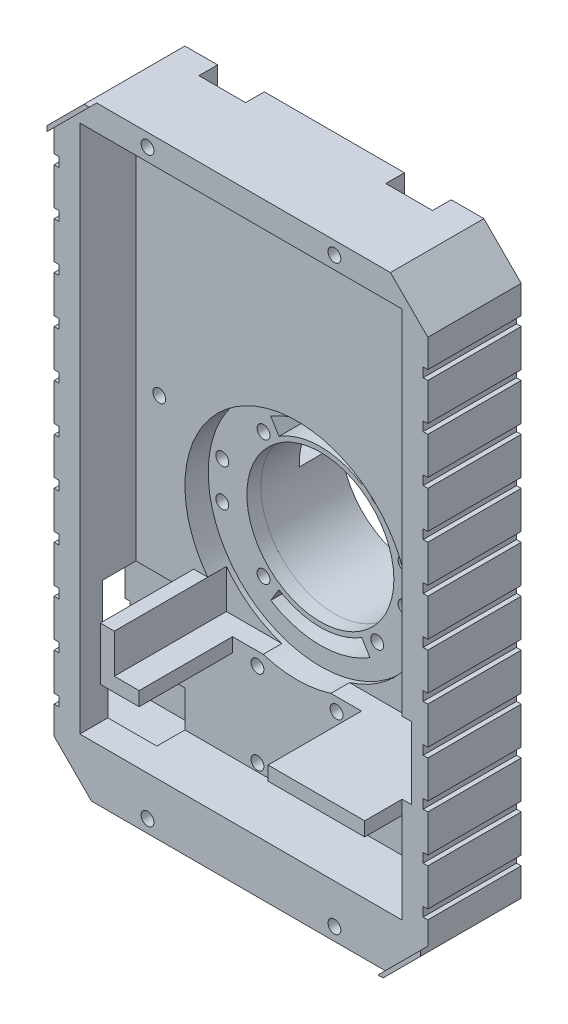
SolidWorks part; units mm, degrees
ref_plane "Front Plane" through (0, 0, 0) normal (0, 0, 1) x (1, 0, 0)
ref_plane "Top Plane" through (0, 0, 0) normal (0, 1, 0) x (1, 0, 0)
ref_plane "Right Plane" through (0, 0, 0) normal (1, 0, 0) x (0, 0, -1)
sketch "Sketch1" plane through (0, 0, 0) normal (0, 0, 1) x (1, 0, 0)
  line L1 (-50.8, -82.55) -> (50.8, -82.55)
  line L2 (-50.8, -82.55) -> (-50.8, 82.55)
  line L3 (-50.8, 82.55) -> (50.8, 82.55)
  line L4 (50.8, -82.55) -> (50.8, 82.55)
  line L5 (-50.8, -82.55) -> (50.8, 82.55) construction
  line L6 (-50.8, 82.55) -> (50.8, -82.55) construction
  point P0 (0, 0)
  dimension "D1" = 101.6
  dimension "D2" = 165.1
extrude "Boss-Extrude1" add sketch "Sketch1" along normal blind 25.4
sketch "Sketch2" plane through (0, 0, 25.4) normal (0, 0, 1) x (1, 0, 0)
  line L0 (50.8, 82.55) -> (-50.8, 82.55) construction
  line L1 (-43.8, -68.326) -> (43.8, -68.326)
  line L2 (-43.8, -68.326) -> (-43.8, 75.55)
  line L3 (-43.8, 75.55) -> (43.8, 75.55)
  line L4 (43.8, -68.326) -> (43.8, 75.55)
  line L5 (-43.8, -68.326) -> (43.8, 75.55) construction
  line L6 (-43.8, 75.55) -> (43.8, -68.326) construction
  line L7 (50.8, -82.55) -> (50.8, 82.55) construction
  line L8 (-50.8, -82.55) -> (50.8, -82.55) construction
  point P0 (0, 0)
  dimension "D1" = 7
  dimension "D2" = 7
  dimension "D3" = 143.876
  dimension "D4" = 87.6
  dimension "D5" = 14.224
extrude "Cut-Extrude1" cut sketch "Sketch2" against normal blind 15.24
sketch "Sketch3" plane through (0, 0, 10.16) normal (0, 0, 1) x (1, 0, 0)
  circle A0 centre (0, -10.8184) radius 19.9875
  dimension "D1" = 39.975
extrude "Cut-Extrude2" cut sketch "Sketch3" against normal through all
sketch "Sketch4" plane through (0, 0, 0) normal (0, 0, -1) x (-1, 0, 0)
  circle A0 centre (0, -10.8184) radius 19.9875
  circle A1 centre (0, -10.8184) radius 26.9875
  dimension "D1" = 53.975
  dimension "D2" = 7
  dimension "D3" = 39.975
extrude "Boss-Extrude2" add sketch "Sketch4" along normal blind 21.844
sketch "Sketch6" plane through (0, 0, -20.955) normal (0, 0, -1) x (-1, 0, 0)
  circle A0 centre (15.4528, 6.1996) radius 1.75
  circle A1 centre (15.4528, -27.8364) radius 1.75
  circle A2 centre (-15.4528, 6.1996) radius 1.75
  circle A3 centre (-15.4528, -27.8364) radius 1.75
  circle A4 centre (0, -10.8184) radius 26.9875 construction
  circle A5 centre (0, -10.8184) radius 26.7375 construction
  dimension "D1" = 3.5
  dimension "D2" = 3.5
  dimension "D3" = 22.987
  dimension "D4" = 22.987
  dimension "D7" = 3.5
  dimension "D8" = 3.5
  dimension "D9" = 22.987
  dimension "D10" = 22.987
extrude "Cut-Extrude3" cut sketch "Sketch6" against normal through all both and the other way through all
sketch "Sketch7" plane through (0, 0, 25.4) normal (0, 0, 1) x (1, 0, 0)
  line L0 (50.8, 82.55) -> (-50.8, 82.55) construction
  line L1 (-50.8, 82.55) -> (-50.8, -82.55) construction
  line L2 (50.8, -82.55) -> (50.8, 82.55) construction
  line L3 (-50.8, -82.55) -> (50.8, -82.55) construction
  circle A0 centre (-25.4, 79.05) radius 1.75
  circle A1 centre (25.4, -79.05) radius 1.75
  circle A2 centre (-25.4, -79.05) radius 1.75
  circle A3 centre (25.4, 79.05) radius 1.75
  dimension "D1" = 3.5
  dimension "D2" = 3.5
  dimension "D3" = 3.5
  dimension "D4" = 3.5
  dimension "D5" = 25.4
  dimension "D6" = 25.4
  dimension "D7" = 25.4
  dimension "D8" = 3.5
  dimension "D9" = 3.5
  dimension "D10" = 3.5
  dimension "D11" = 3.5
  dimension "D12" = 25.4
extrude "Cut-Extrude4" cut sketch "Sketch7" against normal through all
sketch "Sketch8" plane through (0, 0, 0) normal (0, 0, -1) x (-1, 0, 0)
  line L1 (-50.8, 82.55) -> (50.8, 82.55) construction
  line L7 (19.05, 75.55) -> (31.75, 75.55)
  line L8 (50.8, -82.55) -> (-50.8, -82.55) construction
  line L14 (-31.75, 75.55) -> (-19.05, 75.55)
  line L15 (-31.75, 75.55) -> (-31.75, 82.55)
  line L16 (-31.75, 82.55) -> (-19.05, 82.55)
  line L17 (-19.05, 75.55) -> (-19.05, 82.55)
  line L18 (-31.75, 75.55) -> (-19.05, 82.55) construction
  line L19 (-31.75, 82.55) -> (-19.05, 75.55) construction
  line L20 (19.05, -75.55) -> (31.75, -75.55)
  line L21 (19.05, -75.55) -> (19.05, -82.55)
  line L22 (19.05, -82.55) -> (31.75, -82.55)
  line L23 (31.75, -75.55) -> (31.75, -82.55)
  line L24 (19.05, -75.55) -> (31.75, -82.55) construction
  line L25 (19.05, -82.55) -> (31.75, -75.55) construction
  line L26 (19.05, 75.55) -> (19.05, 82.55)
  line L27 (19.05, 82.55) -> (31.75, 82.55)
  line L28 (31.75, 75.55) -> (31.75, 82.55)
  line L29 (19.05, 75.55) -> (31.75, 82.55) construction
  line L30 (19.05, 82.55) -> (31.75, 75.55) construction
  line L31 (-31.75, -75.55) -> (-19.05, -75.55)
  line L32 (-31.75, -75.55) -> (-31.75, -82.55)
  line L33 (-31.75, -82.55) -> (-19.05, -82.55)
  line L34 (-19.05, -75.55) -> (-19.05, -82.55)
  line L35 (-31.75, -75.55) -> (-19.05, -82.55) construction
  line L36 (-31.75, -82.55) -> (-19.05, -75.55) construction
  circle A0 centre (-25.4, 79.05) radius 1.75 construction
  circle A4 centre (25.4, -79.05) radius 1.75 construction
  point P2 (25.4, 79.05)
  point P4 (-25.4, 79.05)
  point P13 (-25.4, -79.05)
  point P14 (25.4, -79.05)
  dimension "D7" = 12.7
  dimension "D1" = 12.7
  dimension "D2" = 12.7
  dimension "D3" = 7
  dimension "D4" = 7
  dimension "D5" = 0
  dimension "D6" = 0
  dimension "D8" = 12.7
extrude "Cut-Extrude5" cut sketch "Sketch8" against normal blind 5.08
sketch "Sketch9" plane through (0, 0, 0) normal (1, 0, 0) x (0, 0, -1)
  line L2 (21.844, -37.8059) -> (21.844, 16.1691) construction
  line L8 (8.1915, 1.8816) -> (21.844, 1.8816)
  line L9 (8.1915, 1.8816) -> (8.1915, -23.5184)
  line L10 (8.1915, -23.5184) -> (21.844, -23.5184)
  line L11 (21.844, 1.8816) -> (21.844, -23.5184)
extrude "Cut-Extrude6" cut sketch "Sketch9" along normal through all
sketch "Sketch10" plane through (0, 0, 0) normal (1, 0, 0) x (0, 0, -1)
  line L0 (21.844, -30.8059) -> (21.844, 9.1691) construction
  line L8 (8.1915, -23.5184) -> (21.844, -23.5184) construction
  line L10 (10.414, -0.0234) -> (10.414, -11.4534)
  line L13 (21.844, -0.0234) -> (21.844, -11.4534)
  line L14 (10.414, -0.0234) -> (21.844, -0.0234)
  line L15 (21.844, -11.4534) -> (10.414, -11.4534)
  dimension "D1" = 11.43
  dimension "D2" = 11.43
  dimension "D3" = 12.065
extrude "Cut-Extrude7" cut sketch "Sketch10" against normal through all
sketch "Sketch11" plane through (0, 0, 10.16) normal (0, 0, 1) x (1, 0, 0)
  circle A1 centre (0, -10.8184) radius 30.48
  dimension "D1" = 60.96
extrude "Cut-Extrude8" cut sketch "Sketch11" against normal blind 6.35
sketch "Sketch12" plane through (0, 0, -21.844) normal (0, 0, -1) x (-1, 0, 0)
  line L0 (-13.4968, 10.8532) -> (-11.2502, 7.2458)
  line L1 (11.2502, 7.2458) -> (13.4968, 10.8532)
  line L2 (-13.4968, -32.49) -> (-11.2502, -28.8826)
  line L4 (11.2502, -28.8826) -> (13.4968, -32.49)
  circle A8 centre (-15.4528, 6.1996) radius 1.75 construction
  circle A9 centre (15.4528, 6.1996) radius 1.75 construction
  arc A10 (-11.2502, -28.8826) -> (11.2502, -28.8826) centre (0, -10.8184) ccw
  arc A11 (-13.4968, -32.49) -> (13.4968, -32.49) centre (0, -10.8184) ccw
  circle A12 centre (-15.4528, -27.8364) radius 1.75 construction
  circle A13 centre (15.4528, -27.8364) radius 1.75 construction
  arc A14 (11.2502, 7.2458) -> (-11.2502, 7.2458) centre (0, -10.8184) ccw
  arc A15 (13.4968, 10.8532) -> (-13.4968, 10.8532) centre (0, -10.8184) ccw
  dimension "D2" = 4.1205
  dimension "D3" = 4.1205
  dimension "D4" = 4.1205
  dimension "D6" = 4.1205
extrude "Cut-Extrude9" cut sketch "Sketch12" against normal up to next
sketch "Sketch13" plane through (0, 0, 0) normal (0, 0, -1) x (-1, 0, 0)
  line L0 (-50.8, -82.55) -> (-50.8, 82.55) construction
  line L1 (-52.07, -62.23) -> (-49.53, -62.23)
  line L2 (-52.07, -62.23) -> (-52.07, -64.77)
  line L3 (-52.07, -64.77) -> (-49.53, -64.77)
  line L4 (-49.53, -62.23) -> (-49.53, -64.77)
  line L5 (-52.07, -62.23) -> (-49.53, -64.77) construction
  line L6 (-52.07, -64.77) -> (-49.53, -62.23) construction
  line L7 (-49.53, -49.53) -> (-49.53, -52.07)
  line L8 (-52.07, -52.07) -> (-49.53, -52.07)
  line L9 (-52.07, -49.53) -> (-52.07, -52.07)
  line L10 (-52.07, -49.53) -> (-49.53, -49.53)
  line L11 (-49.53, -36.83) -> (-49.53, -39.37)
  line L12 (-52.07, -39.37) -> (-49.53, -39.37)
  line L13 (-52.07, -36.83) -> (-52.07, -39.37)
  line L14 (-52.07, -36.83) -> (-49.53, -36.83)
  line L15 (-49.53, -24.13) -> (-49.53, -26.67)
  line L16 (-52.07, -26.67) -> (-49.53, -26.67)
  line L17 (-52.07, -24.13) -> (-52.07, -26.67)
  line L18 (-52.07, -24.13) -> (-49.53, -24.13)
  line L19 (-49.53, -11.43) -> (-49.53, -13.97)
  line L20 (-52.07, -13.97) -> (-49.53, -13.97)
  line L21 (-52.07, -11.43) -> (-52.07, -13.97)
  line L22 (-52.07, -11.43) -> (-49.53, -11.43)
  line L23 (-49.53, 1.27) -> (-49.53, -1.27)
  line L24 (-52.07, -1.27) -> (-49.53, -1.27)
  line L25 (-52.07, 1.27) -> (-52.07, -1.27)
  line L26 (-52.07, 1.27) -> (-49.53, 1.27)
  line L27 (-49.53, 13.97) -> (-49.53, 11.43)
  line L28 (-52.07, 11.43) -> (-49.53, 11.43)
  line L29 (-52.07, 13.97) -> (-52.07, 11.43)
  line L30 (-52.07, 13.97) -> (-49.53, 13.97)
  line L31 (-49.53, 26.67) -> (-49.53, 24.13)
  line L32 (-52.07, 24.13) -> (-49.53, 24.13)
  line L33 (-52.07, 26.67) -> (-52.07, 24.13)
  line L34 (-52.07, 26.67) -> (-49.53, 26.67)
  line L35 (-49.53, 39.37) -> (-49.53, 36.83)
  line L36 (-52.07, 36.83) -> (-49.53, 36.83)
  line L37 (-52.07, 39.37) -> (-52.07, 36.83)
  line L38 (-52.07, 39.37) -> (-49.53, 39.37)
  line L39 (-49.53, 52.07) -> (-49.53, 49.53)
  line L40 (-52.07, 49.53) -> (-49.53, 49.53)
  line L41 (-52.07, 52.07) -> (-52.07, 49.53)
  line L42 (-52.07, 52.07) -> (-49.53, 52.07)
  line L43 (-49.53, 64.77) -> (-49.53, 62.23)
  line L44 (-52.07, 62.23) -> (-49.53, 62.23)
  line L45 (-52.07, 64.77) -> (-52.07, 62.23)
  line L46 (-52.07, 64.77) -> (-49.53, 64.77)
  line L55 (50.8, 82.55) -> (50.8, -82.55) construction
  line L56 (49.53, -64.77) -> (52.07, -64.77)
  line L57 (49.53, -64.77) -> (49.53, -62.23)
  line L58 (49.53, -62.23) -> (52.07, -62.23)
  line L59 (52.07, -64.77) -> (52.07, -62.23)
  line L60 (49.53, -64.77) -> (52.07, -62.23) construction
  line L61 (49.53, -62.23) -> (52.07, -64.77) construction
  line L62 (49.53, -52.07) -> (49.53, -49.53)
  line L63 (49.53, -49.53) -> (52.07, -49.53)
  line L64 (52.07, -52.07) -> (52.07, -49.53)
  line L65 (49.53, -52.07) -> (52.07, -52.07)
  line L66 (49.53, -39.37) -> (49.53, -36.83)
  line L67 (49.53, -36.83) -> (52.07, -36.83)
  line L68 (52.07, -39.37) -> (52.07, -36.83)
  line L69 (49.53, -39.37) -> (52.07, -39.37)
  line L70 (49.53, -26.67) -> (49.53, -24.13)
  line L71 (49.53, -24.13) -> (52.07, -24.13)
  line L72 (52.07, -26.67) -> (52.07, -24.13)
  line L73 (49.53, -26.67) -> (52.07, -26.67)
  line L74 (49.53, -13.97) -> (49.53, -11.43)
  line L75 (49.53, -11.43) -> (52.07, -11.43)
  line L76 (52.07, -13.97) -> (52.07, -11.43)
  line L77 (49.53, -13.97) -> (52.07, -13.97)
  line L78 (49.53, -1.27) -> (49.53, 1.27)
  line L79 (49.53, 1.27) -> (52.07, 1.27)
  line L80 (52.07, -1.27) -> (52.07, 1.27)
  line L81 (49.53, -1.27) -> (52.07, -1.27)
  line L82 (49.53, 11.43) -> (49.53, 13.97)
  line L83 (49.53, 13.97) -> (52.07, 13.97)
  line L84 (52.07, 11.43) -> (52.07, 13.97)
  line L85 (49.53, 11.43) -> (52.07, 11.43)
  line L86 (49.53, 24.13) -> (49.53, 26.67)
  line L87 (49.53, 26.67) -> (52.07, 26.67)
  line L88 (52.07, 24.13) -> (52.07, 26.67)
  line L89 (49.53, 24.13) -> (52.07, 24.13)
  line L90 (49.53, 36.83) -> (49.53, 39.37)
  line L91 (49.53, 39.37) -> (52.07, 39.37)
  line L92 (52.07, 36.83) -> (52.07, 39.37)
  line L93 (49.53, 36.83) -> (52.07, 36.83)
  line L94 (49.53, 49.53) -> (49.53, 52.07)
  line L95 (49.53, 52.07) -> (52.07, 52.07)
  line L96 (52.07, 49.53) -> (52.07, 52.07)
  line L97 (49.53, 49.53) -> (52.07, 49.53)
  line L98 (49.53, 62.23) -> (49.53, 64.77)
  line L99 (49.53, 64.77) -> (52.07, 64.77)
  line L100 (52.07, 62.23) -> (52.07, 64.77)
  line L101 (49.53, 62.23) -> (52.07, 62.23)
  line L110 (-49.53, 77.47) -> (-49.53, 74.93) [skipped]
  line L111 (-52.07, 74.93) -> (-49.53, 74.93) [skipped]
  line L112 (-52.07, 77.47) -> (-52.07, 74.93) [skipped]
  line L113 (-52.07, 77.47) -> (-49.53, 77.47) [skipped]
  line L114 (-49.53, 90.17) -> (-49.53, 87.63) [skipped]
  line L115 (-52.07, 87.63) -> (-49.53, 87.63) [skipped]
  line L116 (-52.07, 90.17) -> (-52.07, 87.63) [skipped]
  line L117 (-52.07, 90.17) -> (-49.53, 90.17) [skipped]
  line L118 (49.53, 74.93) -> (49.53, 77.47) [skipped]
  line L119 (49.53, 77.47) -> (52.07, 77.47) [skipped]
  line L120 (52.07, 74.93) -> (52.07, 77.47) [skipped]
  line L121 (49.53, 74.93) -> (52.07, 74.93) [skipped]
  line L122 (49.53, 87.63) -> (49.53, 90.17) [skipped]
  line L123 (49.53, 90.17) -> (52.07, 90.17) [skipped]
  line L124 (52.07, 87.63) -> (52.07, 90.17) [skipped]
  line L125 (49.53, 87.63) -> (52.07, 87.63) [skipped]
  point P0 (-50.8, -63.5)
  point P8 (50.8, -63.5)
  dimension "D1" = 2.54
  dimension "D2" = 2.54
  dimension "D3" = 17.78
  dimension "D5" = 2.54
  dimension "D6" = 2.54
  dimension "D7" = 17.78
  dimension "D9" = 10.16
  dimension "D4" = 13
  dimension "D8" = 13
extrude "Cut-Extrude10" cut sketch "Sketch13" against normal up to next
chamfer "Chamfer9" distance 10.16 angle 45 4 edges at (50.8, 82.55, 12.7) (50.8, -82.55, 12.7) (-50.8, -82.55, 12.7) (-50.8, 82.55, 12.7)
sketch "Sketch14" plane through (0, 0, 3.81) normal (0, 0, 1) x (1, 0, 0)
  circle A2 centre (-26.67, -5.7384) radius 1.75
  circle A3 centre (-26.67, -15.8984) radius 1.75
  circle A4 centre (0, -10.8184) radius 19.9875 construction
  circle A5 centre (22.86, -5.7384) radius 1.75
  circle A6 centre (22.86, -15.8984) radius 1.75
  dimension "D1" = 26.67
  dimension "D2" = 26.67
  dimension "D3" = 3.5
  dimension "D4" = 3.5
  dimension "D6" = 22.86
  dimension "D7" = 3.5
  dimension "D8" = 3.5
  dimension "D5" = 22.86
extrude "Cut-Extrude11" cut sketch "Sketch14" against normal blind 2.54
sketch "Sketch15" plane through (0, 0, 10.16) normal (0, 0, 1) x (1, 0, 0)
  line L0 (-43.8, 75.55) -> (-43.8, -68.326) construction
  line L1 (43.8, 75.55) -> (-43.8, 75.55) construction
  line L2 (43.8, -68.326) -> (43.8, 75.55) construction
  circle A0 centre (-37.45, 69.2) radius 1.75
  circle A1 centre (-37.45, 6.9216) radius 1.75
  circle A2 centre (38.085, 69.2) radius 1.75
  circle A3 centre (38.085, 6.9216) radius 1.75
  dimension "D1" = 3.5
  dimension "D2" = 3.5
  dimension "D3" = 3.5
  dimension "D4" = 3.5
  dimension "D5" = 6.35
  dimension "D6" = 6.35
  dimension "D7" = 6.35
  dimension "D8" = 5.715
  dimension "D9" = 6.35
  dimension "D10" = 5.715
extrude "Cut-Extrude12" cut sketch "Sketch15" against normal blind 5.08
sketch "Sketch16" plane through (0, 0, 25.4) normal (0, 0, 1) x (1, 0, 0)
  line L2 (-45.0129, 76.7629) -> (-50.8, 70.9758)
  line L3 (-50.8, 72.39) -> (-50.8, 64.77) construction
  line L4 (-50.8, 70.9758) -> (-50.8, 72.39)
  line L5 (-50.8, 72.39) -> (-40.64, 82.55)
  line L6 (-45.0129, 76.7629) -> (-39.2258, 82.55)
  line L7 (40.64, 82.55) -> (-40.64, 82.55) construction
  line L8 (-39.2258, 82.55) -> (-40.64, 82.55)
  line L10 (45.0129, -76.7629) -> (39.2258, -82.55)
  line L11 (-40.64, -82.55) -> (40.64, -82.55) construction
  line L12 (39.2258, -82.55) -> (40.64, -82.55)
  line L13 (40.64, -82.55) -> (50.8, -72.39)
  line L14 (45.0129, -76.7629) -> (50.8, -70.9758)
  line L15 (50.8, -72.39) -> (50.8, -64.77) construction
  line L16 (50.8, -70.9758) -> (50.8, -72.39)
extrude "Boss-Extrude3" add sketch "Sketch16" along normal blind 2
sketch "Sketch18" plane through (-50.8, 0, 0) normal (-1, 0, 0) x (0, 0, 1)
  line L0 (0, -39.37) -> (0, -49.53) construction
  line L1 (0, -52.07) -> (0, -62.23) construction
  line L4 (6.096, -53.7) -> (19.304, -53.7)
  line L5 (6.096, -53.7) -> (6.096, -35.2)
  line L6 (6.096, -35.2) -> (19.304, -35.2)
  line L7 (19.304, -53.7) -> (19.304, -35.2)
  line L8 (6.096, -53.7) -> (19.304, -35.2) construction
  line L9 (6.096, -35.2) -> (19.304, -53.7) construction
  line L12 (7.62, -68.58) -> (17.78, -68.58)
  line L13 (7.62, -68.58) -> (7.62, -58.42)
  line L14 (7.62, -58.42) -> (17.78, -58.42)
  line L15 (17.78, -68.58) -> (17.78, -58.42)
  line L16 (7.62, -68.58) -> (17.78, -58.42) construction
  line L17 (7.62, -58.42) -> (17.78, -68.58) construction
  point P6 (12.7, -44.45)
  point P11 (12.7, -63.5)
  dimension "D1" = 13.208
  dimension "D2" = 18.5
  dimension "D3" = 12.7
  dimension "D4" = 12.7
  dimension "D5" = 10.16
  dimension "D6" = 10.16
extrude "Cut-Extrude14" cut sketch "Sketch18" against normal blind 20.32
sketch "Sketch19" plane through (0, 0, 10.16) normal (0, 0, 1) x (1, 0, 0)
  circle A2 centre (-10.7595, -43.4177) radius 1.75
  circle A3 centre (10.7595, -43.4177) radius 1.75
  circle A4 centre (10.1245, -66.2067) radius 1.75
  circle A5 centre (-10.7595, -66.2067) radius 1.75
  point P8 (0, -54.8122)
  dimension "D3" = 3.5
  dimension "D4" = 3.5
  dimension "D5" = 3.5
  dimension "D6" = 3.5
extrude "Cut-Extrude15" cut sketch "Sketch19" against normal blind 5.08
sketch "Sketch20" plane through (0, 0, 0) normal (1, 0, 0) x (0, 0, -1)
  line L5 (0, -11.43) -> (0, -1.27) construction
  line L12 (0, -17.2998) -> (6.35, -17.2998)
  line L13 (0, -17.2998) -> (0, -3.3298)
  line L14 (0, -3.3298) -> (6.35, -3.3298)
  line L15 (6.35, -17.2998) -> (6.35, -3.3298)
  line L16 (0, -17.2998) -> (6.35, -3.3298) construction
  line L17 (0, -3.3298) -> (6.35, -17.2998) construction
  point P4 (3.175, -10.3148)
  dimension "D1" = 0
  dimension "D2" = 6.35
  dimension "D3" = 13.97
extrude "Cut-Extrude16" cut sketch "Sketch20" along normal blind 21.59
sketch "Sketch21" plane through (0, 0, 10.16) normal (0, 0, 1) x (1, 0, 0)
  line L0 (43.8, -68.326) -> (43.8, 75.55) construction
  line L1 (43.8, -39.878) -> (-24.272, -39.878)
  line L2 (43.8, -39.878) -> (43.8, -20.32)
  line L3 (43.8, -20.32) -> (-24.272, -20.32)
  line L4 (-24.272, -39.878) -> (-24.272, -20.32)
  dimension "D2" = 0
  dimension "D3" = 68.072
extrude "Cut-Extrude17" cut sketch "Sketch21" against normal blind 5.08
sketch "Sketch22" plane through (0, 0, 10.16) normal (0, 0, 1) x (1, 0, 0)
  line L0 (-24.272, -29.2548) -> (-28.082, -29.2548)
  line L1 (-28.082, -29.2548) -> (-28.082, -43.688)
  line L2 (-28.082, -43.688) -> (-17.5243, -43.688)
  line L3 (-17.5243, -43.688) -> (-17.5243, -39.878)
  line L4 (-24.272, -39.878) -> (-9.1962, -39.878) construction
  line L5 (-24.272, -29.2548) -> (-24.272, -39.878) construction
  line L6 (17.5243, -39.878) -> (17.5243, -43.688)
  line L7 (9.1962, -39.878) -> (43.8, -39.878) construction
  line L8 (17.5243, -43.688) -> (43.8, -43.688)
  line L9 (43.8, -68.326) -> (43.8, -39.878) construction
  line L10 (-24.272, -29.2548) -> (-24.272, -39.878)
  line L11 (-24.272, -39.878) -> (-17.5243, -39.878)
  line L12 (17.5243, -39.878) -> (43.8, -39.878)
  line L13 (43.8, -39.878) -> (43.8, -43.688)
  circle A0 centre (-10.7595, -43.4177) radius 1.75 construction
  circle A1 centre (10.7595, -43.4177) radius 1.75 construction
  dimension "D5" = 6.7648
  dimension "D1" = 3.81
  dimension "D2" = 3.81
  dimension "D3" = 3.81
  dimension "D4" = 6.7648
extrude "Boss-Extrude4" add sketch "Sketch22" along normal blind 25.4
sketch "Sketch23" plane through (43.8, 0, 0) normal (-1, 0, 0) x (0, 0, 1)
  line L0 (5.08, -20.32) -> (5.08, -39.878)
  line L1 (5.08, -39.878) -> (25.4, -39.878)
  line L2 (25.4, -39.878) -> (25.4, -20.32)
  line L3 (25.4, -39.878) -> (25.4, 75.55) construction
  line L4 (25.4, -20.32) -> (5.08, -20.32)
extrude "Cut-Extrude18" cut sketch "Sketch23" against normal blind 2.54
sketch "Sketch24" plane through (0, 0, 3.81) normal (0, 0, 1) x (1, 0, 0)
  line L1 (18.4528, 1.8816) -> (23.8125, 1.8816)
  line L2 (18.4528, 1.8816) -> (18.4528, 7.4696)
  line L3 (18.4528, 7.4696) -> (19.8463, 7.4696)
  circle A3 centre (15.4528, 6.1996) radius 1.75 construction
  arc A8 (23.8125, 1.8816) -> (19.8463, 7.4696) centre (0, -10.8184) ccw
  point P0 (21.4184, 4.6756)
  dimension "D1" = 3
  dimension "D2" = 1.27
  dimension "D3" = 0
  dimension "D4" = 5.588
  dimension "D5" = 5.3597
extrude "Cut-Extrude19" cut sketch "Sketch24" against normal through all
